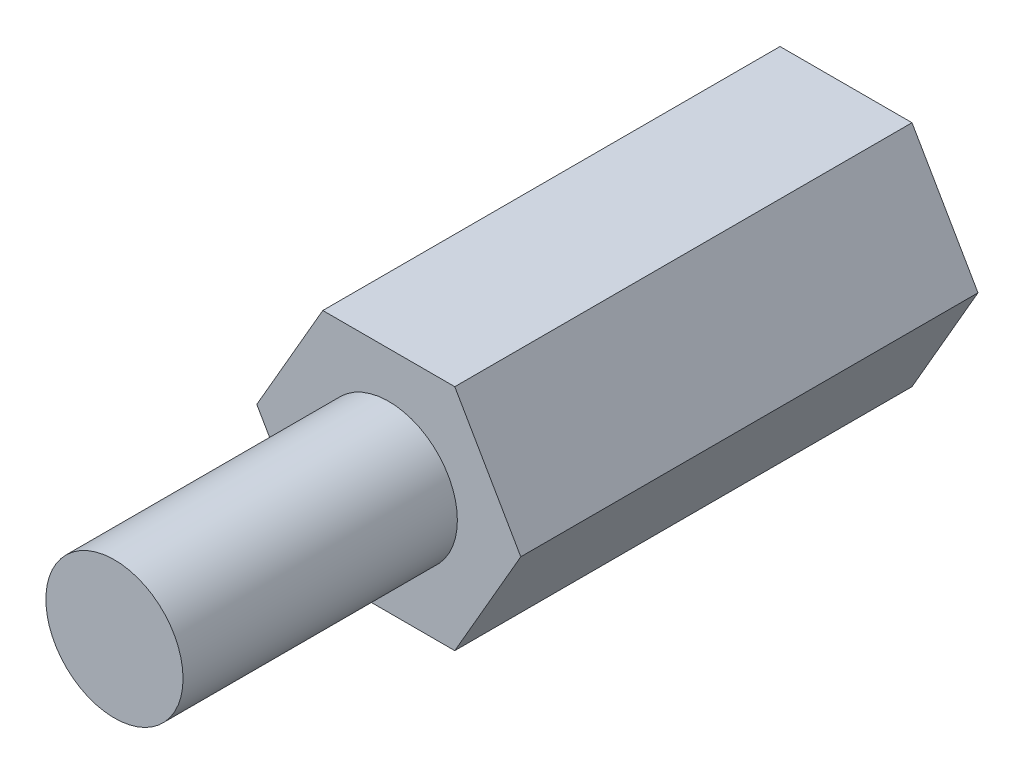
SolidWorks part; units mm, degrees
material "Brass"
ref_plane "Front Plane" through (0, 0, 0) normal (0, 0, 1) x (1, 0, 0)
ref_plane "Top Plane" through (0, 0, 0) normal (0, 1, 0) x (1, 0, 0)
ref_plane "Right Plane" through (0, 0, 0) normal (1, 0, 0) x (0, 0, -1)
sketch "Sketch1" plane through (0, 0, 0) normal (0, 0, 1) x (1, 0, 0)
  line L1 (-1.4434, 2.5) -> (-2.8868, 0)
  line L2 (-2.8868, 0) -> (-1.4434, -2.5)
  line L3 (-1.4434, -2.5) -> (1.4434, -2.5)
  line L4 (1.4434, -2.5) -> (2.8868, 0)
  line L5 (2.8868, 0) -> (1.4434, 2.5)
  line L6 (1.4434, 2.5) -> (-1.4434, 2.5)
  circle A0 centre (0, 0) radius 2.5 construction
  dimension "D1" = 5
extrude "Boss-Extrude1" add sketch "Sketch1" along normal blind 10
sketch "Sketch2" plane through (0, 0, 10) normal (0, 0, 1) x (1, 0, 0)
  circle A0 centre (0, 0) radius 1.5
extrude "Boss-Extrude2" add sketch "Sketch2" along normal blind 6
cosmetic thread "Cosmetic Thread1"
hole_wizard "M3x0.5 Tapped Hole1" positions "Sketch6" profile "Sketch5" tap size "M3x0.5" standard "ANSI Metric"
sketch "Sketch6" plane through (0, 0, 0) normal (0, 0, -1) x (-1, 0, 0)
  point P0 (0, 0)
sketch "Sketch5" plane through (0, 0, 0) normal (1, 0, 0) x (0, 1, 0)
  line L0 (0, 0) -> (0, 8.7511)
  line L1 (0, 8.7511) -> (1.25, 8)
  line L2 (1.25, 8) -> (1.25, 0)
  line L5 (1.25, 0) -> (0, 0)
  line L10 (0, 8.7511) -> (-1.25, 8) construction
  line L11 (0, -6.35) -> (0, 107.95) construction
  dimension "Tap Drill Dia." = 2.5
  dimension "Tap Drill Depth" = 8
  dimension "Drill Angle" = 118
cosmetic thread "Hole Thread1"
